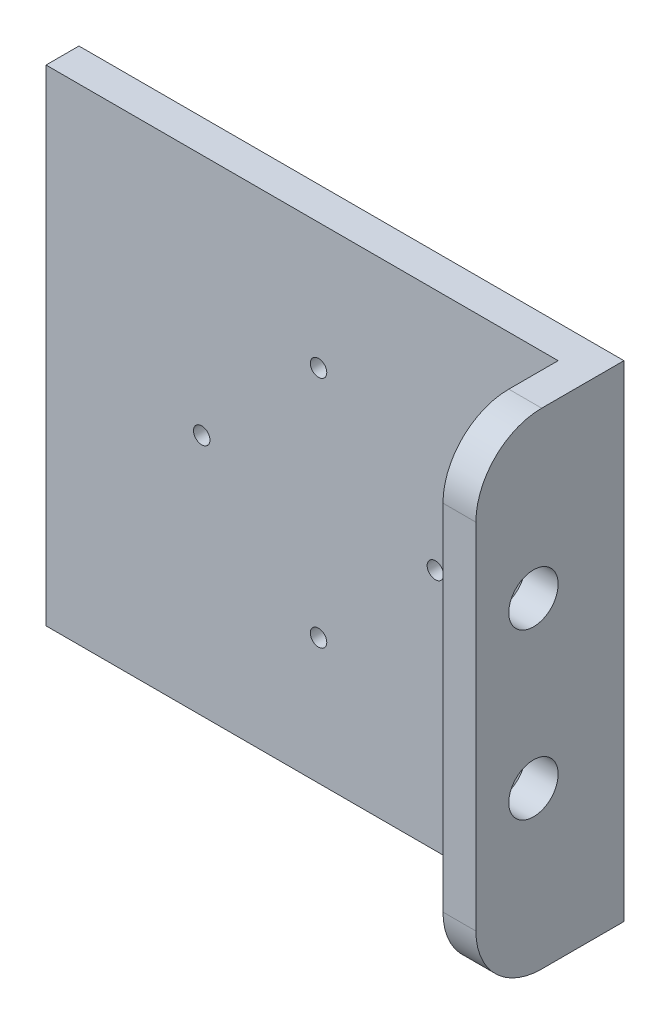
SolidWorks part; units mm, degrees
ref_plane "前视基准面" through (0, 0, 0) normal (0, 0, 1) x (1, 0, 0)
ref_plane "上视基准面" through (0, 0, 0) normal (0, 1, 0) x (1, 0, 0)
ref_plane "右视基准面" through (0, 0, 0) normal (1, 0, 0) x (0, 0, -1)
sketch "草图1" plane through (0, 0, 0) normal (0, 0, 1) x (1, 0, 0)
  line L1 (-16.5621, 14.7609) -> (16.5621, 14.7609)
  line L2 (-16.5621, 14.7609) -> (-16.5621, -14.7609)
  line L3 (-16.5621, -14.7609) -> (16.5621, -14.7609)
  line L4 (16.5621, 14.7609) -> (16.5621, -14.7609)
  line L5 (-16.5621, 14.7609) -> (16.5621, -14.7609) construction
  line L6 (-16.5621, -14.7609) -> (16.5621, 14.7609) construction
  circle A0 centre (0, 7.1) radius 0.5 construction
  circle A1 centre (0, 7.1) radius 0.5
  circle A2 centre (7.1, 0) radius 0.5 construction
  circle A3 centre (7.1, 0) radius 0.5
  circle A4 centre (0, -7.1) radius 0.5 construction
  circle A5 centre (0, -7.1) radius 0.5
  circle A6 centre (-7.1, 0) radius 0.5 construction
  circle A7 centre (-7.1, 0) radius 0.5
  point P0 (0, 0)
extrude "凸台-拉伸1" add sketch "草图1" along normal blind 2
sketch "草图2" plane through (16.5621, 0, 0) normal (1, 0, 0) x (0, 0, -1)
  line L0 (-2, 14.7609) -> (0, 14.7609) construction
  line L1 (-5, -14.7609) -> (0, -14.7609)
  line L2 (-9, -10.7609) -> (-9, 10.7609)
  line L3 (-5, 14.7609) -> (0, 14.7609)
  line L4 (0, -14.7609) -> (0, 14.7609)
  line L5 (-9, -14.7609) -> (0, 14.7609) construction
  line L6 (-9, 14.7609) -> (0, -14.7609) construction
  line L7 (0, -14.7609) -> (0, 14.7609) construction
  arc A0 (-9, 10.7609) -> (-5, 14.7609) centre (-5, 10.7609) cw
  arc A1 (-5, -14.7609) -> (-9, -10.7609) centre (-5, -10.7609) cw
  point P0 (-4.5, 0)
  dimension "D1" = 4
  dimension "D2" = 5
extrude "凸台-拉伸2" add sketch "草图2" against normal blind 2
sketch "草图3" plane through (16.5621, 0, 0) normal (1, 0, 0) x (0, 0, -1)
  arc A0 (-7, -5) -> (-4, -5) centre (-5.5, -5) ccw construction
  arc A1 (-4, -5) -> (-7, -5) centre (-5.5, -5) ccw construction
  arc A2 (-7, 5) -> (-4, 5) centre (-5.5, 5) ccw construction
  arc A3 (-4, 5) -> (-7, 5) centre (-5.5, 5) ccw construction
  arc A4 (-7, -5) -> (-4, -5) centre (-5.5, -5) ccw
  arc A5 (-4, -5) -> (-7, -5) centre (-5.5, -5) ccw
  arc A6 (-7, 5) -> (-4, 5) centre (-5.5, 5) ccw
  arc A7 (-4, 5) -> (-7, 5) centre (-5.5, 5) ccw
extrude "切除-拉伸1" cut sketch "草图3" against normal blind 6
